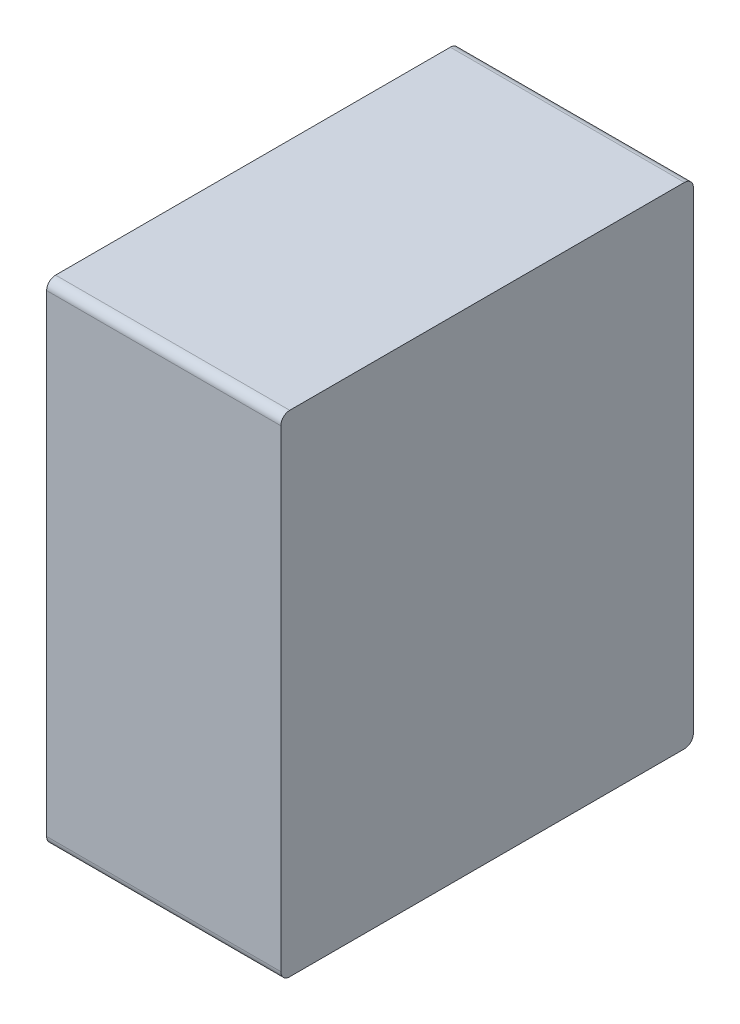
SolidWorks part; units mm, degrees
ref_plane "前视基准面" through (0, 0, 0) normal (0, 0, 1) x (1, 0, 0)
ref_plane "上视基准面" through (0, 0, 0) normal (0, 1, 0) x (1, 0, 0)
ref_plane "右视基准面" through (0, 0, 0) normal (1, 0, 0) x (0, 0, -1)
sketch "草图1" plane through (0, 0, 0) normal (1, 0, 0) x (0, 0, -1)
  line L1 (0, 0) -> (185, 0)
  line L2 (0, 0) -> (0, -220)
  line L3 (0, -220) -> (185, -220)
  line L4 (185, 0) -> (185, -220)
extrude "凸台-拉伸1" add sketch "草图1" along normal blind 105
fillet "圆角1" radius 4 4 edges at (52.5, 0, -185) (52.5, -220, -185) (52.5, -220, 0) (52.5, 0, 0)
